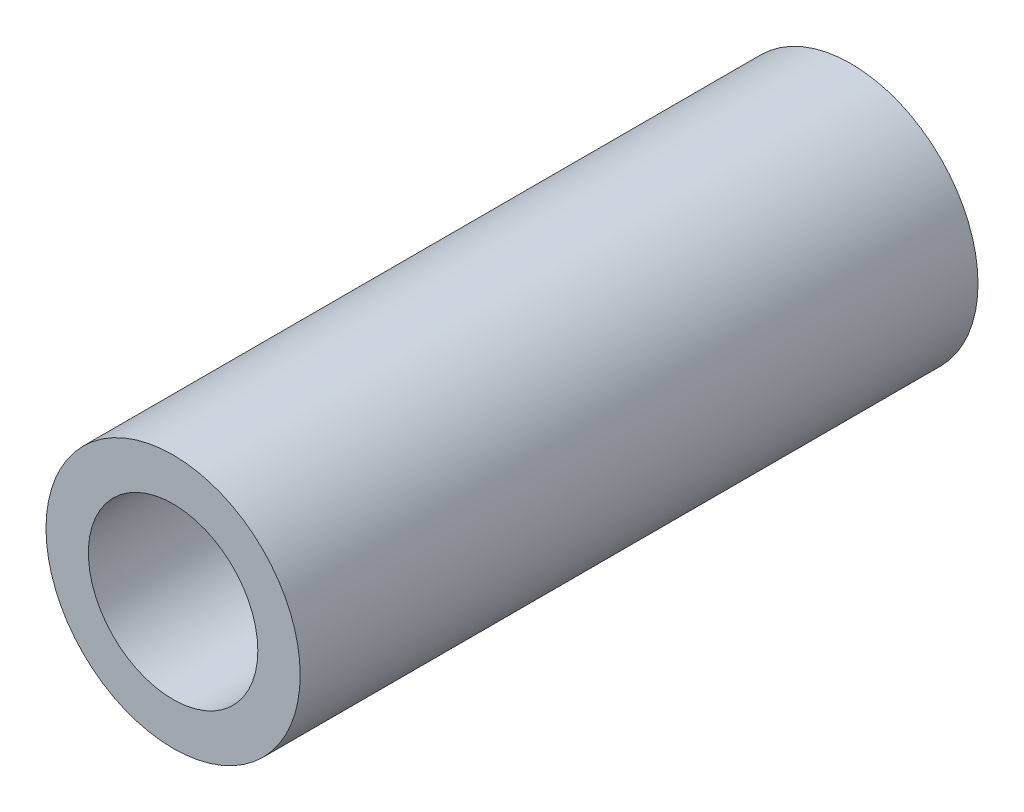
SolidWorks part; units mm, degrees
ref_plane "Ön Düzlem" through (0, 0, 0) normal (0, 0, 1) x (1, 0, 0)
ref_plane "Üst Düzlem" through (0, 0, 0) normal (0, 1, 0) x (1, 0, 0)
ref_plane "Sağ Düzlem" through (0, 0, 0) normal (1, 0, 0) x (0, 0, -1)
sketch "Sketch1" plane through (0, 0, 0) normal (0, 0, 1) x (1, 0, 0)
  circle A0 centre (0, 0) radius 7.5
  dimension "D1" = 15
extrude "Boss-Extrude1" add sketch "Sketch1" along normal blind 40
sketch "Sketch2" plane through (0, 0, 40) normal (0, 0, 1) x (1, 0, 0)
  circle A0 centre (0, 0) radius 5
  dimension "D1" = 10
extrude "Cut-Extrude1" cut sketch "Sketch2" against normal blind 10
sketch "Sketch3" plane through (0, 0, 0) normal (0, 0, -1) x (-1, 0, 0)
  circle A0 centre (0, 0) radius 5
  dimension "D1" = 10
extrude "Cut-Extrude2" cut sketch "Sketch3" against normal blind 10
ref_plane "Plane1" through (0, 0, 12) normal (0, 0, -1) x (-1, 0, 0)
ref_plane "Plane2" through (0, 0, 28) normal (0, 0, 1) x (1, 0, 0)
sketch "Sketch4" plane through (0, 0, 28) normal (0, 0, 1) x (1, 0, 0)
  circle A0 centre (0, 0) radius 5
  circle A1 centre (0, 0) radius 9.497
